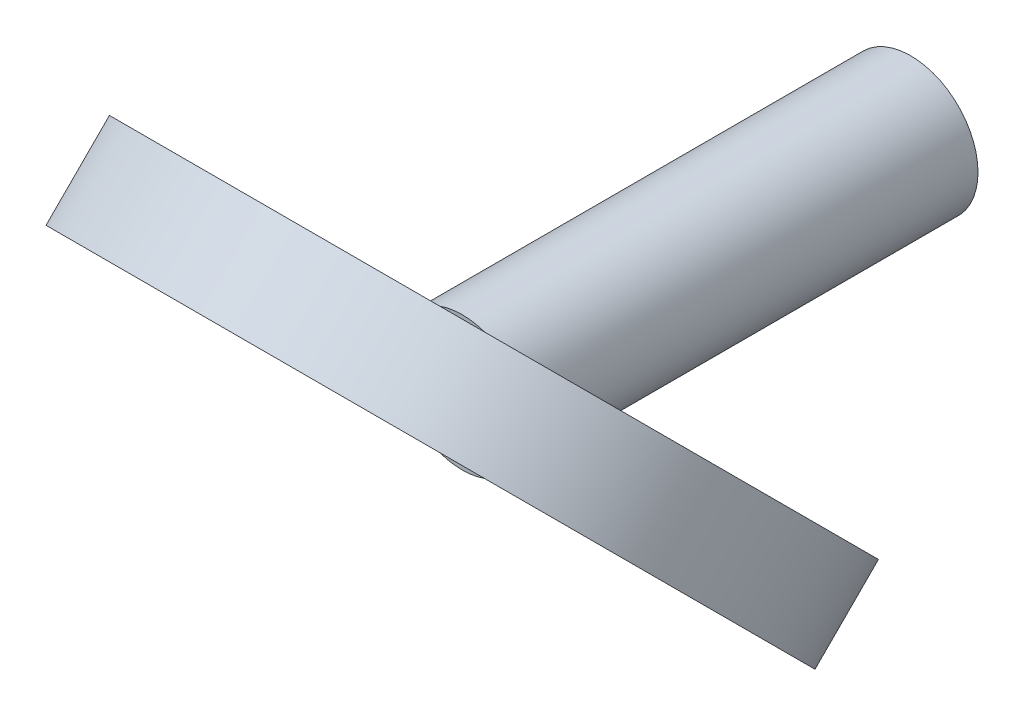
SolidWorks part; units mm, degrees
ref_plane "Front Plane" through (0, 0, 0) normal (0, 0, 1) x (1, 0, 0)
ref_plane "Top Plane" through (0, 0, 0) normal (0, 1, 0) x (1, 0, 0)
ref_plane "Right Plane" through (0, 0, 0) normal (1, 0, 0) x (0, 0, -1)
sketch "Sketch1" plane through (0, 0, 0) normal (0, 0, 1) x (1, 0, 0)
  circle A1 centre (0, 0) radius 7.5
  dimension "D1" = 15
extrude "Boss-Extrude1" add sketch "Sketch1" against normal blind 50
ref_plane "Plane1" through (0, 0, 0) normal (0, -0.7071, 0.7071) x (1, 0, 0)
sketch "Sketch3" plane through (0, 0, 0) normal (0, -0.7071, 0.7071) x (1, 0, 0)
  circle A0 centre (0, 0) radius 35
  dimension "D1" = 70
extrude "Boss-Extrude2" add sketch "Sketch3" along normal mid plane 10
sketch "Sketch4" plane through (0, 0, -50) normal (0, 0, -1) x (-1, 0, 0)
  circle A0 centre (0, 0) radius 2.5
  dimension "D1" = 5
extrude "Cut-Extrude1" cut sketch "Sketch4" against normal blind 5
